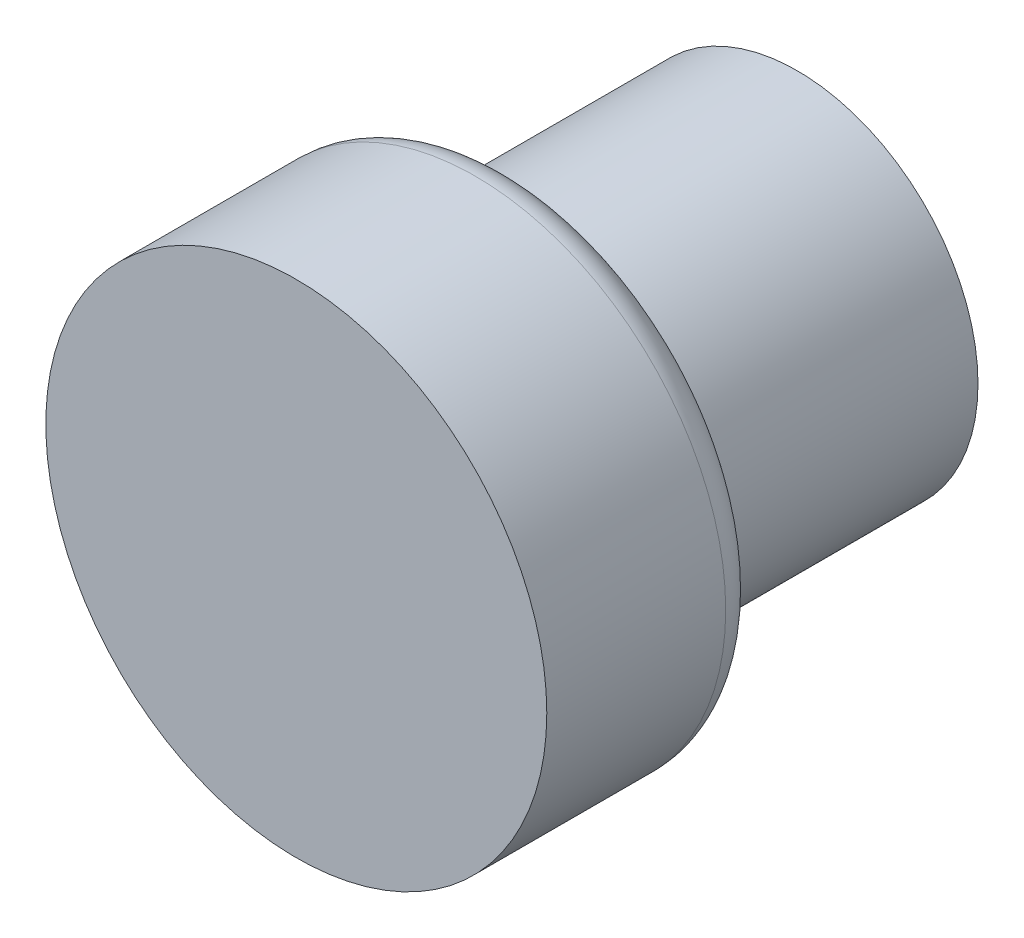
SolidWorks part; units mm, degrees
material "Custom Plastic"
ref_plane "Front Plane" through (0, 0, 0) normal (0, 0, 1) x (1, 0, 0)
ref_plane "Top Plane" through (0, 0, 0) normal (0, 1, 0) x (1, 0, 0)
ref_plane "Right Plane" through (0, 0, 0) normal (1, 0, 0) x (0, 0, -1)
sketch "Sketch1" plane through (0, 0, 0) normal (0, 0, 1) x (1, 0, 0)
  circle A0 centre (0, 0) radius 2.525
  dimension "D1" = 5.05
extrude "Boss-Extrude1" add sketch "Sketch1" along normal blind 4 contours A0
sketch "Sketch2" plane through (0, 0, 4) normal (0, 0, 1) x (1, 0, 0)
  circle A0 centre (0, 0) radius 3.5
  dimension "D1" = 7
extrude "Boss-Extrude2" add sketch "Sketch2" along normal blind 3 contours A0
fillet "Fillet1" radius 0.5 1 edges at (3.5, 0, 4)
